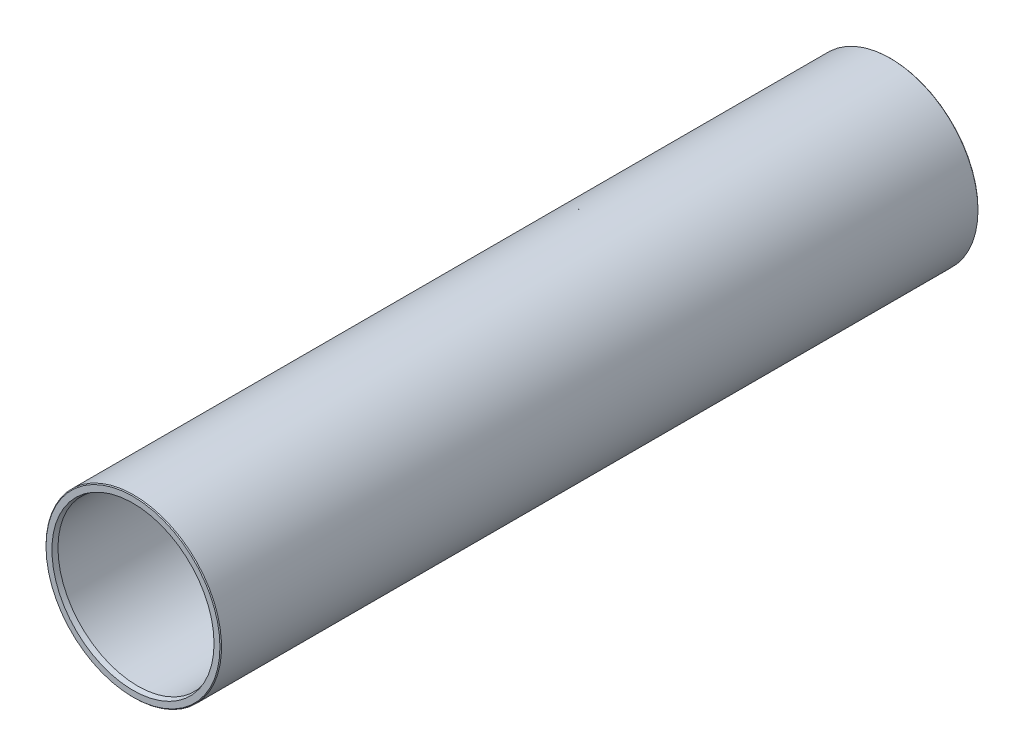
SolidWorks part; units mm, degrees
material "Acrylic (Medium-high impact)"
ref_plane "Front Plane" through (0, 0, 0) normal (0, 0, 1) x (1, 0, 0)
ref_plane "Top Plane" through (0, 0, 0) normal (0, 1, 0) x (1, 0, 0)
ref_plane "Right Plane" through (0, 0, 0) normal (1, 0, 0) x (0, 0, -1)
sketch "Sketch1" plane through (0, 0, 0) normal (0, 0, 1) x (1, 0, 0)
  circle A0 centre (0, 0) radius 55
  circle A1 centre (0, 0) radius 50
  dimension "D1" = 110
  dimension "D2" = 100
extrude "Tube Body" add sketch "Sketch1" along normal mid plane 475
chamfer "Boresink_Leadin" distance 0.8 distance2 3 2 edges at (50, 0, 237.5) (50, 0, -237.5)
chamfer "Boresink_Leadin." distance 0.8 distance2 3 1 edges at (50, 0, -236.7)
chamfer "OD_Edge_Break" distance 0.5 angle 45 2 edges at (55, 0, 237.5) (55, 0, -237.5)
equation "\"OD\"= 110mm"
equation "\"ID\"= 100mm"
equation "\"L\"= 475mm"
equation "\"D1@Sketch1\"=\"OD\""
equation "\"D2@Sketch1\"=\"ID\""
equation "\"D1@Tube Body\"=\"L\""
